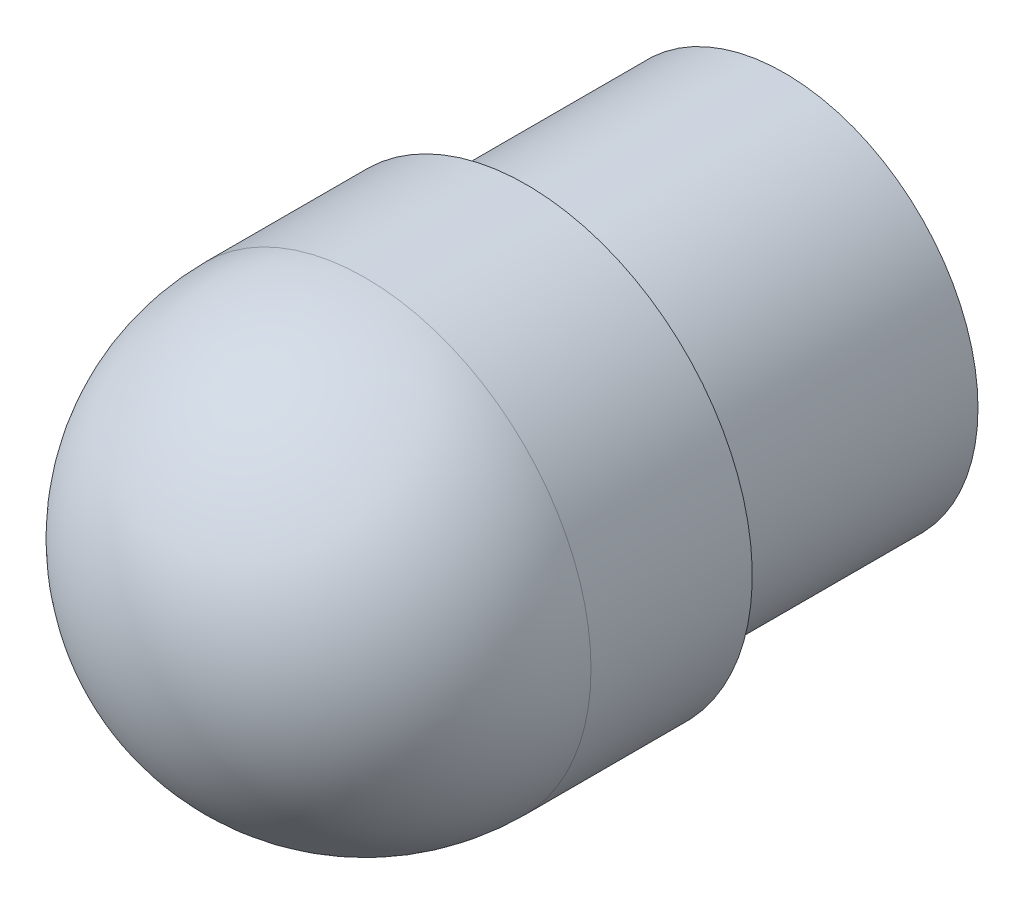
SolidWorks part; units mm, degrees
ref_plane "Front Plane" through (0, 0, 0) normal (0, 0, 1) x (1, 0, 0)
ref_plane "Top Plane" through (0, 0, 0) normal (0, 1, 0) x (1, 0, 0)
ref_plane "Right Plane" through (0, 0, 0) normal (1, 0, 0) x (0, 0, -1)
sketch "Sketch7" plane through (0, 0, 0) normal (0, 0, 1) x (1, 0, 0)
  circle A0 centre (0, 0) radius 381
  dimension "D1" = 762
extrude "Boss-Extrude3" add sketch "Sketch7" along normal blind 508
sketch "Sketch8" plane through (0, 0, 508) normal (0, 0, 1) x (1, 0, 0)
  circle A0 centre (0, 0) radius 444.5
  dimension "D1" = 889
extrude "Boss-Extrude4" add sketch "Sketch8" along normal blind 317.5
sketch "Sketch9" plane through (0, 0, 825.5) normal (0, 0, 1) x (1, 0, 0)
  line L0 (0, 444.5) -> (0, -444.5)
  arc A0 (0, 444.5) -> (0, -444.5) centre (0, 0) ccw
  circle A1 centre (0, 0) radius 444.5 construction
revolve "Revolve1" add sketch "Sketch9" angle 360 about L0
